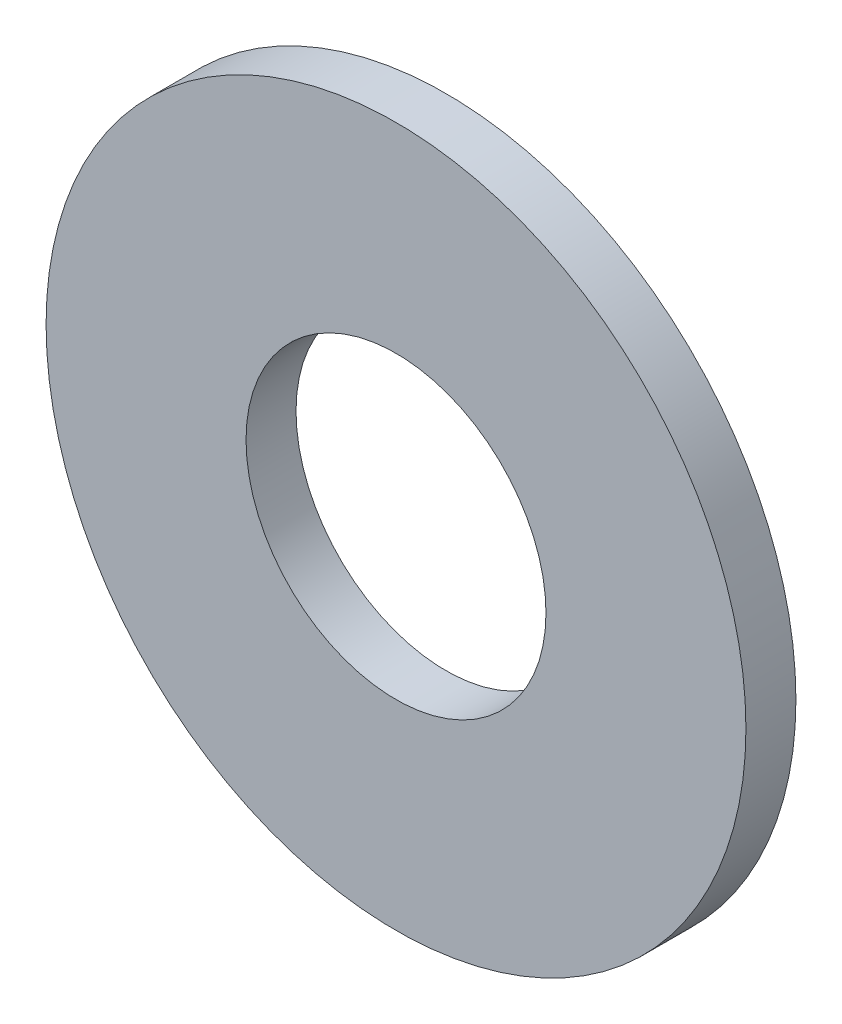
SolidWorks part; units mm, degrees
ref_plane "Plan de face" through (0, 0, 0) normal (0, 0, 1) x (1, 0, 0)
ref_plane "Plan de dessus" through (0, 0, 0) normal (0, 1, 0) x (1, 0, 0)
ref_plane "Plan de droite" through (0, 0, 0) normal (1, 0, 0) x (0, 0, -1)
sketch "Esquisse1" plane through (0, 0, 0) normal (0, 0, 1) x (1, 0, 0)
  circle A0 centre (0, 0) radius 7
  circle A1 centre (0, 0) radius 3
  dimension "D1" = 6
  dimension "D2" = 14
extrude "Boss.-Extru.1" add sketch "Esquisse1" along normal blind 1
